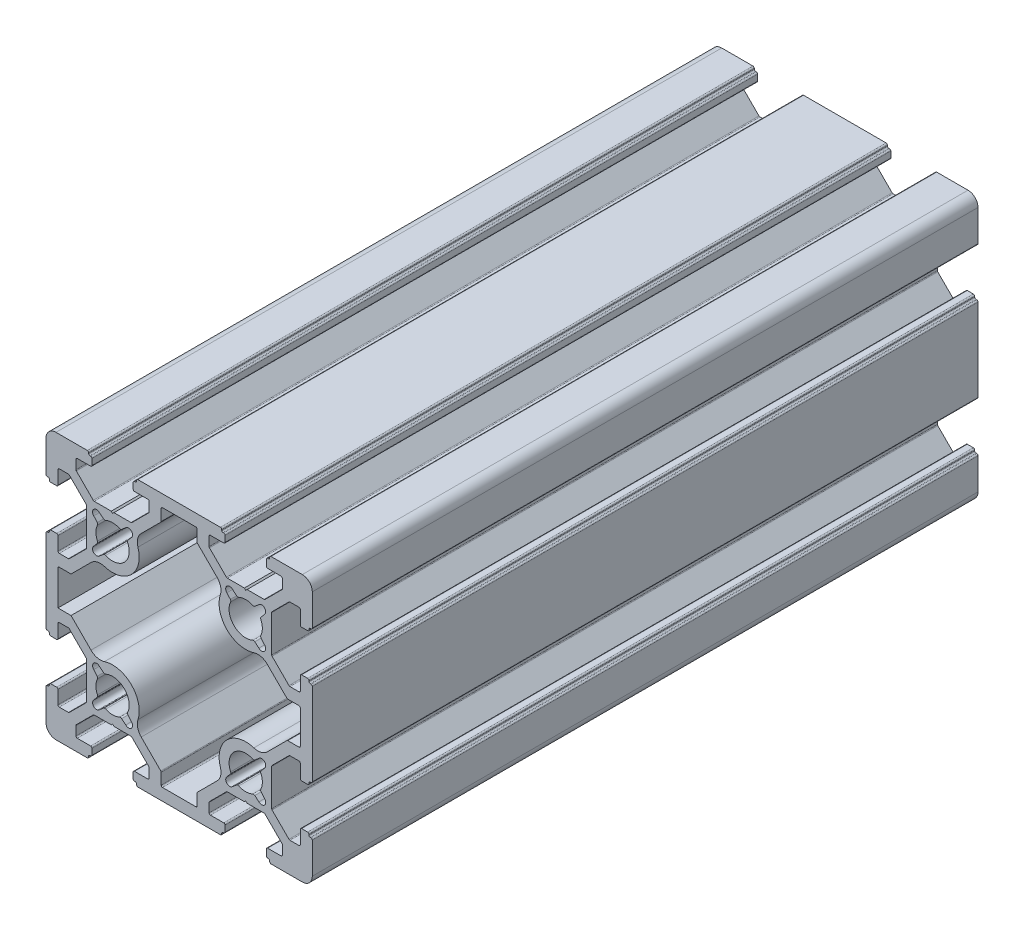
SolidWorks part; units mm, degrees
ref_plane "前视基准面" through (0, 0, 0) normal (0, 0, 1) x (1, 0, 0)
ref_plane "上视基准面" through (0, 0, 0) normal (0, 1, 0) x (1, 0, 0)
ref_plane "右视基准面" through (0, 0, 0) normal (1, 0, 0) x (0, 0, -1)
sketch "草图1" plane through (0, 0, 0) normal (0, 0, 1) x (1, 0, 0)
  line B0 (42.4612, 11.6) -> (43.3612, 11.6)
  line B1 (43.5612, 11.8) -> (43.5612, 11.9)
  line B2 (43.7612, 12.1) -> (43.8612, 12.1)
  line B3 (44.0612, 12.3) -> (44.0612, 24.7)
  line B4 (43.8612, 24.9) -> (43.7612, 24.9)
  line B5 (43.5612, 25.1) -> (43.5612, 25.2)
  line B6 (43.3612, 25.4) -> (42.4612, 25.4)
  line B7 (42.2612, 25.2) -> (42.2612, 23.2)
  line B8 (42.0612, 23) -> (40.7047, 23)
  line B9 (40.5633, 23.0586) -> (38.0198, 25.6021)
  line B10 (37.9612, 25.7435) -> (37.9612, 31.2565)
  line B11 (38.0198, 31.3979) -> (40.5633, 33.9414)
  line B12 (40.7047, 34) -> (42.0612, 34)
  line B13 (42.2612, 33.8) -> (42.2612, 31.8)
  line B14 (42.4612, 31.6) -> (43.3612, 31.6)
  line B15 (43.5612, 31.8) -> (43.5612, 31.9)
  line B16 (43.7612, 32.1) -> (43.8612, 32.1)
  line B17 (44.0612, 32.3) -> (44.0612, 37)
  line B18 (42.5612, 38.5) -> (37.8612, 38.5)
  line B19 (37.6612, 38.3) -> (37.6612, 38.2)
  line B20 (37.4612, 38) -> (37.3612, 38)
  line B21 (37.1612, 37.8) -> (37.1612, 36.9)
  line B22 (37.3612, 36.7) -> (39.3612, 36.7)
  line B23 (39.5612, 36.5) -> (39.5612, 35.1435)
  line B24 (39.5026, 35.0021) -> (36.9591, 32.4586)
  line B25 (36.8177, 32.4) -> (34.2612, 32.4)
  line B26 (34.2612, 32.4) -> (34.0612, 32.2)
  line B27 (34.0612, 32.2) -> (33.8612, 32.4)
  line B28 (33.8612, 32.4) -> (31.3047, 32.4)
  line B29 (31.1633, 32.4586) -> (28.6198, 35.0021)
  line B30 (28.5612, 35.1435) -> (28.5612, 36.5)
  line B31 (28.7612, 36.7) -> (30.7612, 36.7)
  line B32 (30.9612, 36.9) -> (30.9612, 37.8)
  line B33 (30.7612, 38) -> (30.6612, 38)
  line B34 (30.4612, 38.2) -> (30.4612, 38.3)
  line B35 (30.2612, 38.5) -> (17.8612, 38.5)
  line B36 (17.6612, 38.3) -> (17.6612, 38.2)
  line B37 (17.4612, 38) -> (17.3612, 38)
  line B38 (17.1612, 37.8) -> (17.1612, 36.9)
  line B39 (17.3612, 36.7) -> (19.3612, 36.7)
  line B40 (19.5612, 36.5) -> (19.5612, 35.1435)
  line B41 (19.5026, 35.0021) -> (16.9591, 32.4586)
  line B42 (16.8177, 32.4) -> (14.2612, 32.4)
  line B43 (14.2612, 32.4) -> (14.0612, 32.2)
  line B44 (14.0612, 32.2) -> (13.8612, 32.4)
  line B45 (13.8612, 32.4) -> (11.3047, 32.4)
  line B46 (11.1633, 32.4586) -> (8.6198, 35.0021)
  line B47 (8.5612, 35.1435) -> (8.5612, 36.5)
  line B48 (8.7612, 36.7) -> (10.7612, 36.7)
  line B49 (10.9612, 36.9) -> (10.9612, 37.8)
  line B50 (10.7612, 38) -> (10.6612, 38)
  line B51 (10.4612, 38.2) -> (10.4612, 38.3)
  line B52 (10.2612, 38.5) -> (5.5612, 38.5)
  line B53 (4.0612, 37) -> (4.0612, 32.3)
  line B54 (4.2612, 32.1) -> (4.3612, 32.1)
  line B55 (4.5612, 31.9) -> (4.5612, 31.8)
  line B56 (4.7612, 31.6) -> (5.6612, 31.6)
  line B57 (5.8612, 31.8) -> (5.8612, 33.8)
  line B58 (6.0612, 34) -> (7.4177, 34)
  line B59 (7.5591, 33.9414) -> (10.1026, 31.3979)
  line B60 (10.1612, 31.2565) -> (10.1612, 25.7435)
  line B61 (10.1026, 25.6021) -> (7.5591, 23.0586)
  line B62 (7.4177, 23) -> (6.0612, 23)
  line B63 (5.8612, 23.2) -> (5.8612, 25.2)
  line B64 (5.6612, 25.4) -> (4.7612, 25.4)
  line B65 (4.5612, 25.2) -> (4.5612, 25.1)
  line B66 (4.3612, 24.9) -> (4.2612, 24.9)
  line B67 (4.0612, 24.7) -> (4.0612, 12.3)
  line B68 (4.2612, 12.1) -> (4.3612, 12.1)
  line B69 (4.5612, 11.9) -> (4.5612, 11.8)
  line B70 (4.7612, 11.6) -> (5.6612, 11.6)
  line B71 (5.8612, 11.8) -> (5.8612, 13.8)
  line B72 (6.0612, 14) -> (7.4177, 14)
  line B73 (7.5591, 13.9414) -> (10.1026, 11.3979)
  line B74 (10.1612, 11.2565) -> (10.1612, 5.7435)
  line B75 (10.1026, 5.6021) -> (7.5591, 3.0586)
  line B76 (7.4177, 3) -> (6.0612, 3)
  line B77 (5.8612, 3.2) -> (5.8612, 5.2)
  line B78 (5.6612, 5.4) -> (4.7612, 5.4)
  line B79 (4.5612, 5.2) -> (4.5612, 5.1)
  line B80 (4.3612, 4.9) -> (4.2612, 4.9)
  line B81 (4.0612, 4.7) -> (4.0612, 0)
  line B82 (5.5612, -1.5) -> (10.2612, -1.5)
  line B83 (10.4612, -1.3) -> (10.4612, -1.2)
  line B84 (10.6612, -1) -> (10.7612, -1)
  line B85 (10.9612, -0.8) -> (10.9612, 0.1)
  line B86 (10.7612, 0.3) -> (8.7612, 0.3)
  line B87 (8.5612, 0.5) -> (8.5612, 1.8565)
  line B88 (8.6198, 1.9979) -> (11.1633, 4.5414)
  line B89 (11.3047, 4.6) -> (13.8612, 4.6)
  line B90 (13.8612, 4.6) -> (14.0612, 4.8)
  line B91 (14.0612, 4.8) -> (14.2612, 4.6)
  line B92 (14.2612, 4.6) -> (16.8177, 4.6)
  line B93 (16.9591, 4.5414) -> (19.5026, 1.9979)
  line B94 (19.5612, 1.8565) -> (19.5612, 0.5)
  line B95 (19.3612, 0.3) -> (17.3612, 0.3)
  line B96 (17.1612, 0.1) -> (17.1612, -0.8)
  line B97 (17.3612, -1) -> (17.4612, -1)
  line B98 (17.6612, -1.2) -> (17.6612, -1.3)
  line B99 (17.8612, -1.5) -> (30.2612, -1.5)
  line B100 (30.4612, -1.3) -> (30.4612, -1.2)
  line B101 (30.6612, -1) -> (30.7612, -1)
  line B102 (30.9612, -0.8) -> (30.9612, 0.1)
  line B103 (30.7612, 0.3) -> (28.7612, 0.3)
  line B104 (28.5612, 0.5) -> (28.5612, 1.8565)
  line B105 (28.6198, 1.9979) -> (31.1633, 4.5414)
  line B106 (31.3047, 4.6) -> (33.8612, 4.6)
  line B107 (33.8612, 4.6) -> (34.0612, 4.8)
  line B108 (34.0612, 4.8) -> (34.2612, 4.6)
  line B109 (34.2612, 4.6) -> (36.8177, 4.6)
  line B110 (36.9591, 4.5414) -> (39.5026, 1.9979)
  line B111 (39.5612, 1.8565) -> (39.5612, 0.5)
  line B112 (39.3612, 0.3) -> (37.3612, 0.3)
  line B113 (37.1612, 0.1) -> (37.1612, -0.8)
  line B114 (37.3612, -1) -> (37.4612, -1)
  line B115 (37.6612, -1.2) -> (37.6612, -1.3)
  line B116 (37.8612, -1.5) -> (42.5612, -1.5)
  line B117 (44.0612, 0) -> (44.0612, 4.7)
  line B118 (43.8612, 4.9) -> (43.7612, 4.9)
  line B119 (43.5612, 5.1) -> (43.5612, 5.2)
  line B120 (43.3612, 5.4) -> (42.4612, 5.4)
  line B121 (42.2612, 5.2) -> (42.2612, 3.2)
  line B122 (42.0612, 3) -> (40.7047, 3)
  line B123 (40.5633, 3.0586) -> (38.0198, 5.6021)
  line B124 (37.9612, 5.7435) -> (37.9612, 11.2565)
  line B125 (38.0198, 11.3979) -> (40.5633, 13.9414)
  line B126 (40.7047, 14) -> (42.0612, 14)
  line B127 (42.2612, 13.8) -> (42.2612, 11.8)
  line B128 (31.7484, 7.1346) -> (31.2328, 6.5201)
  line B129 (32.0813, 5.6716) -> (32.6958, 6.1872)
  line B130 (35.4266, 6.1872) -> (36.0411, 5.6716)
  line B131 (36.8896, 6.5201) -> (36.374, 7.1346)
  line B132 (36.374, 9.8654) -> (36.8896, 10.4799)
  line B133 (36.0411, 11.3284) -> (35.4266, 10.8128)
  line B134 (35.4266, 26.1872) -> (36.0411, 25.6716)
  line B135 (36.8896, 26.5201) -> (36.374, 27.1346)
  line B136 (36.374, 29.8654) -> (36.8896, 30.4799)
  line B137 (36.0411, 31.3284) -> (35.4266, 30.8128)
  line B138 (32.6958, 30.8128) -> (32.0813, 31.3284)
  line B139 (31.2328, 30.4799) -> (31.7484, 29.8654)
  line B140 (42.2612, 16) -> (42.2612, 21)
  line B141 (42.0612, 21.2) -> (40.3834, 21.2)
  line B142 (40.242, 21.2586) -> (37.3016, 24.1989)
  line B143 (29.7601, 31.7404) -> (26.8198, 34.6808)
  line B144 (26.7612, 34.8222) -> (26.7612, 36.5)
  line B145 (26.5612, 36.7) -> (21.5612, 36.7)
  line B146 (21.3612, 36.5) -> (21.3612, 34.8222)
  line B147 (21.3026, 34.6808) -> (18.3623, 31.7404)
  line B148 (10.8207, 24.1989) -> (7.8804, 21.2586)
  line B149 (7.739, 21.2) -> (6.0612, 21.2)
  line B150 (5.8612, 21) -> (5.8612, 15.8)
  line B151 (5.8612, 15.8) -> (7.8219, 15.8)
  line B152 (7.8219, 15.8) -> (10.8207, 12.8011)
  line B153 (18.3623, 5.2596) -> (21.3026, 2.3192)
  line B154 (21.3612, 2.1778) -> (21.3612, 0.5)
  line B155 (21.5612, 0.3) -> (26.5612, 0.3)
  line B156 (26.7612, 0.5) -> (26.7612, 2.1778)
  line B157 (26.8198, 2.3192) -> (29.7601, 5.2596)
  line B158 (37.3016, 12.8011) -> (40.242, 15.7414)
  line B159 (40.3834, 15.8) -> (42.0612, 15.8)
  line B160 (12.6958, 10.8128) -> (12.0813, 11.3284)
  line B161 (11.2328, 10.4799) -> (11.7484, 9.8654)
  line B162 (11.7484, 7.1346) -> (11.2328, 6.5201)
  line B163 (12.0813, 5.6716) -> (12.6958, 6.1872)
  line B164 (15.4266, 6.1872) -> (16.0411, 5.6716)
  line B165 (16.8896, 6.5201) -> (16.374, 7.1346)
  line B166 (16.374, 29.8654) -> (16.8896, 30.4799)
  line B167 (16.0411, 31.3284) -> (15.4266, 30.8128)
  line B168 (12.6958, 30.8128) -> (12.0813, 31.3284)
  line B169 (11.2328, 30.4799) -> (11.7484, 29.8654)
  line B170 (11.7484, 27.1346) -> (11.2328, 26.5201)
  line B171 (12.0813, 25.6716) -> (12.6958, 26.1872)
  arc B172 (42.2612, 11.8) -> (42.4612, 11.6) centre (42.4612, 11.8) ccw
  arc B173 (43.3612, 11.6) -> (43.5612, 11.8) centre (43.3612, 11.8) ccw
  arc B174 (43.7612, 12.1) -> (43.5612, 11.9) centre (43.7612, 11.9) ccw
  arc B175 (43.8612, 12.1) -> (44.0612, 12.3) centre (43.8612, 12.3) ccw
  arc B176 (44.0612, 24.7) -> (43.8612, 24.9) centre (43.8612, 24.7) ccw
  arc B177 (43.5612, 25.1) -> (43.7612, 24.9) centre (43.7612, 25.1) ccw
  arc B178 (43.5612, 25.2) -> (43.3612, 25.4) centre (43.3612, 25.2) ccw
  arc B179 (42.4612, 25.4) -> (42.2612, 25.2) centre (42.4612, 25.2) ccw
  arc B180 (42.0612, 23) -> (42.2612, 23.2) centre (42.0612, 23.2) ccw
  arc B181 (40.5633, 23.0586) -> (40.7047, 23) centre (40.7047, 23.2) ccw
  arc B182 (37.9612, 25.7435) -> (38.0198, 25.6021) centre (38.1612, 25.7435) ccw
  arc B183 (38.0198, 31.3979) -> (37.9612, 31.2565) centre (38.1612, 31.2565) ccw
  arc B184 (40.7047, 34) -> (40.5633, 33.9414) centre (40.7047, 33.8) ccw
  arc B185 (42.2612, 33.8) -> (42.0612, 34) centre (42.0612, 33.8) ccw
  arc B186 (42.2612, 31.8) -> (42.4612, 31.6) centre (42.4612, 31.8) ccw
  arc B187 (43.3612, 31.6) -> (43.5612, 31.8) centre (43.3612, 31.8) ccw
  arc B188 (43.7612, 32.1) -> (43.5612, 31.9) centre (43.7612, 31.9) ccw
  arc B189 (43.8612, 32.1) -> (44.0612, 32.3) centre (43.8612, 32.3) ccw
  arc B190 (44.0612, 37) -> (42.5612, 38.5) centre (42.5612, 37) ccw
  arc B191 (37.8612, 38.5) -> (37.6612, 38.3) centre (37.8612, 38.3) ccw
  arc B192 (37.4612, 38) -> (37.6612, 38.2) centre (37.4612, 38.2) ccw
  arc B193 (37.3612, 38) -> (37.1612, 37.8) centre (37.3612, 37.8) ccw
  arc B194 (37.1612, 36.9) -> (37.3612, 36.7) centre (37.3612, 36.9) ccw
  arc B195 (39.5612, 36.5) -> (39.3612, 36.7) centre (39.3612, 36.5) ccw
  arc B196 (39.5026, 35.0021) -> (39.5612, 35.1435) centre (39.3612, 35.1435) ccw
  arc B197 (36.8177, 32.4) -> (36.9591, 32.4586) centre (36.8177, 32.6) ccw
  arc B198 (31.1633, 32.4586) -> (31.3047, 32.4) centre (31.3047, 32.6) ccw
  arc B199 (28.5612, 35.1435) -> (28.6198, 35.0021) centre (28.7612, 35.1435) ccw
  arc B200 (28.7612, 36.7) -> (28.5612, 36.5) centre (28.7612, 36.5) ccw
  arc B201 (30.7612, 36.7) -> (30.9612, 36.9) centre (30.7612, 36.9) ccw
  arc B202 (30.9612, 37.8) -> (30.7612, 38) centre (30.7612, 37.8) ccw
  arc B203 (30.4612, 38.2) -> (30.6612, 38) centre (30.6612, 38.2) ccw
  arc B204 (30.4612, 38.3) -> (30.2612, 38.5) centre (30.2612, 38.3) ccw
  arc B205 (17.8612, 38.5) -> (17.6612, 38.3) centre (17.8612, 38.3) ccw
  arc B206 (17.4612, 38) -> (17.6612, 38.2) centre (17.4612, 38.2) ccw
  arc B207 (17.3612, 38) -> (17.1612, 37.8) centre (17.3612, 37.8) ccw
  arc B208 (17.1612, 36.9) -> (17.3612, 36.7) centre (17.3612, 36.9) ccw
  arc B209 (19.5612, 36.5) -> (19.3612, 36.7) centre (19.3612, 36.5) ccw
  arc B210 (19.5026, 35.0021) -> (19.5612, 35.1435) centre (19.3612, 35.1435) ccw
  arc B211 (16.8177, 32.4) -> (16.9591, 32.4586) centre (16.8177, 32.6) ccw
  arc B212 (11.1633, 32.4586) -> (11.3047, 32.4) centre (11.3047, 32.6) ccw
  arc B213 (8.5612, 35.1435) -> (8.6198, 35.0021) centre (8.7612, 35.1435) ccw
  arc B214 (8.7612, 36.7) -> (8.5612, 36.5) centre (8.7612, 36.5) ccw
  arc B215 (10.7612, 36.7) -> (10.9612, 36.9) centre (10.7612, 36.9) ccw
  arc B216 (10.9612, 37.8) -> (10.7612, 38) centre (10.7612, 37.8) ccw
  arc B217 (10.4612, 38.2) -> (10.6612, 38) centre (10.6612, 38.2) ccw
  arc B218 (10.4612, 38.3) -> (10.2612, 38.5) centre (10.2612, 38.3) ccw
  arc B219 (5.5612, 38.5) -> (4.0612, 37) centre (5.5612, 37) ccw
  arc B220 (4.0612, 32.3) -> (4.2612, 32.1) centre (4.2612, 32.3) ccw
  arc B221 (4.5612, 31.9) -> (4.3612, 32.1) centre (4.3612, 31.9) ccw
  arc B222 (4.5612, 31.8) -> (4.7612, 31.6) centre (4.7612, 31.8) ccw
  arc B223 (5.6612, 31.6) -> (5.8612, 31.8) centre (5.6612, 31.8) ccw
  arc B224 (6.0612, 34) -> (5.8612, 33.8) centre (6.0612, 33.8) ccw
  arc B225 (7.5591, 33.9414) -> (7.4177, 34) centre (7.4177, 33.8) ccw
  arc B226 (10.1612, 31.2565) -> (10.1026, 31.3979) centre (9.9612, 31.2565) ccw
  arc B227 (10.1026, 25.6021) -> (10.1612, 25.7435) centre (9.9612, 25.7435) ccw
  arc B228 (7.4177, 23) -> (7.5591, 23.0586) centre (7.4177, 23.2) ccw
  arc B229 (5.8612, 23.2) -> (6.0612, 23) centre (6.0612, 23.2) ccw
  arc B230 (5.8612, 25.2) -> (5.6612, 25.4) centre (5.6612, 25.2) ccw
  arc B231 (4.7612, 25.4) -> (4.5612, 25.2) centre (4.7612, 25.2) ccw
  arc B232 (4.3612, 24.9) -> (4.5612, 25.1) centre (4.3612, 25.1) ccw
  arc B233 (4.2612, 24.9) -> (4.0612, 24.7) centre (4.2612, 24.7) ccw
  arc B234 (4.0612, 12.3) -> (4.2612, 12.1) centre (4.2612, 12.3) ccw
  arc B235 (4.5612, 11.9) -> (4.3612, 12.1) centre (4.3612, 11.9) ccw
  arc B236 (4.5612, 11.8) -> (4.7612, 11.6) centre (4.7612, 11.8) ccw
  arc B237 (5.6612, 11.6) -> (5.8612, 11.8) centre (5.6612, 11.8) ccw
  arc B238 (6.0612, 14) -> (5.8612, 13.8) centre (6.0612, 13.8) ccw
  arc B239 (7.5591, 13.9414) -> (7.4177, 14) centre (7.4177, 13.8) ccw
  arc B240 (10.1612, 11.2565) -> (10.1026, 11.3979) centre (9.9612, 11.2565) ccw
  arc B241 (10.1026, 5.6021) -> (10.1612, 5.7435) centre (9.9612, 5.7435) ccw
  arc B242 (7.4177, 3) -> (7.5591, 3.0586) centre (7.4177, 3.2) ccw
  arc B243 (5.8612, 3.2) -> (6.0612, 3) centre (6.0612, 3.2) ccw
  arc B244 (5.8612, 5.2) -> (5.6612, 5.4) centre (5.6612, 5.2) ccw
  arc B245 (4.7612, 5.4) -> (4.5612, 5.2) centre (4.7612, 5.2) ccw
  arc B246 (4.3612, 4.9) -> (4.5612, 5.1) centre (4.3612, 5.1) ccw
  arc B247 (4.2612, 4.9) -> (4.0612, 4.7) centre (4.2612, 4.7) ccw
  arc B248 (4.0612, 0) -> (5.5612, -1.5) centre (5.5612, 0) ccw
  arc B249 (10.2612, -1.5) -> (10.4612, -1.3) centre (10.2612, -1.3) ccw
  arc B250 (10.6612, -1) -> (10.4612, -1.2) centre (10.6612, -1.2) ccw
  arc B251 (10.7612, -1) -> (10.9612, -0.8) centre (10.7612, -0.8) ccw
  arc B252 (10.9612, 0.1) -> (10.7612, 0.3) centre (10.7612, 0.1) ccw
  arc B253 (8.5612, 0.5) -> (8.7612, 0.3) centre (8.7612, 0.5) ccw
  arc B254 (8.6198, 1.9979) -> (8.5612, 1.8565) centre (8.7612, 1.8565) ccw
  arc B255 (11.3047, 4.6) -> (11.1633, 4.5414) centre (11.3047, 4.4) ccw
  arc B256 (16.9591, 4.5414) -> (16.8177, 4.6) centre (16.8177, 4.4) ccw
  arc B257 (19.5612, 1.8565) -> (19.5026, 1.9979) centre (19.3612, 1.8565) ccw
  arc B258 (19.3612, 0.3) -> (19.5612, 0.5) centre (19.3612, 0.5) ccw
  arc B259 (17.3612, 0.3) -> (17.1612, 0.1) centre (17.3612, 0.1) ccw
  arc B260 (17.1612, -0.8) -> (17.3612, -1) centre (17.3612, -0.8) ccw
  arc B261 (17.6612, -1.2) -> (17.4612, -1) centre (17.4612, -1.2) ccw
  arc B262 (17.6612, -1.3) -> (17.8612, -1.5) centre (17.8612, -1.3) ccw
  arc B263 (30.2612, -1.5) -> (30.4612, -1.3) centre (30.2612, -1.3) ccw
  arc B264 (30.6612, -1) -> (30.4612, -1.2) centre (30.6612, -1.2) ccw
  arc B265 (30.7612, -1) -> (30.9612, -0.8) centre (30.7612, -0.8) ccw
  arc B266 (30.9612, 0.1) -> (30.7612, 0.3) centre (30.7612, 0.1) ccw
  arc B267 (28.5612, 0.5) -> (28.7612, 0.3) centre (28.7612, 0.5) ccw
  arc B268 (28.6198, 1.9979) -> (28.5612, 1.8565) centre (28.7612, 1.8565) ccw
  arc B269 (31.3047, 4.6) -> (31.1633, 4.5414) centre (31.3047, 4.4) ccw
  arc B270 (36.9591, 4.5414) -> (36.8177, 4.6) centre (36.8177, 4.4) ccw
  arc B271 (39.5612, 1.8565) -> (39.5026, 1.9979) centre (39.3612, 1.8565) ccw
  arc B272 (39.3612, 0.3) -> (39.5612, 0.5) centre (39.3612, 0.5) ccw
  arc B273 (37.3612, 0.3) -> (37.1612, 0.1) centre (37.3612, 0.1) ccw
  arc B274 (37.1612, -0.8) -> (37.3612, -1) centre (37.3612, -0.8) ccw
  arc B275 (37.6612, -1.2) -> (37.4612, -1) centre (37.4612, -1.2) ccw
  arc B276 (37.6612, -1.3) -> (37.8612, -1.5) centre (37.8612, -1.3) ccw
  arc B277 (42.5612, -1.5) -> (44.0612, 0) centre (42.5612, 0) ccw
  arc B278 (44.0612, 4.7) -> (43.8612, 4.9) centre (43.8612, 4.7) ccw
  arc B279 (43.5612, 5.1) -> (43.7612, 4.9) centre (43.7612, 5.1) ccw
  arc B280 (43.5612, 5.2) -> (43.3612, 5.4) centre (43.3612, 5.2) ccw
  arc B281 (42.4612, 5.4) -> (42.2612, 5.2) centre (42.4612, 5.2) ccw
  arc B282 (42.0612, 3) -> (42.2612, 3.2) centre (42.0612, 3.2) ccw
  arc B283 (40.5633, 3.0586) -> (40.7047, 3) centre (40.7047, 3.2) ccw
  arc B284 (37.9612, 5.7435) -> (38.0198, 5.6021) centre (38.1612, 5.7435) ccw
  arc B285 (38.0198, 11.3979) -> (37.9612, 11.2565) centre (38.1612, 11.2565) ccw
  arc B286 (40.7047, 14) -> (40.5633, 13.9414) centre (40.7047, 13.8) ccw
  arc B287 (42.2612, 13.8) -> (42.0612, 14) centre (42.0612, 13.8) ccw
  arc B288 (35.1082, 10.7702) -> (35.4266, 10.8128) centre (35.2338, 11.0426) ccw
  arc B289 (35.1082, 10.7702) -> (31.791, 7.453) centre (34.0612, 8.5) ccw
  arc B290 (31.7484, 7.1346) -> (31.791, 7.453) centre (31.5186, 7.3274) ccw
  arc B291 (31.2328, 6.5201) -> (32.0813, 5.6716) centre (31.657, 6.0958) ccw
  arc B292 (33.0142, 6.2298) -> (32.6958, 6.1872) centre (32.8886, 5.9574) ccw
  arc B293 (33.0142, 6.2298) -> (35.1082, 6.2298) centre (34.0612, 8.5) ccw
  arc B294 (35.4266, 6.1872) -> (35.1082, 6.2298) centre (35.2338, 5.9574) ccw
  arc B295 (36.0411, 5.6716) -> (36.8896, 6.5201) centre (36.4654, 6.0958) ccw
  arc B296 (36.3314, 7.453) -> (36.374, 7.1346) centre (36.6038, 7.3274) ccw
  arc B297 (36.3314, 7.453) -> (36.3314, 9.547) centre (34.0612, 8.5) ccw
  arc B298 (36.374, 9.8654) -> (36.3314, 9.547) centre (36.6038, 9.6726) ccw
  arc B299 (36.8896, 10.4799) -> (36.0411, 11.3284) centre (36.4654, 10.9042) ccw
  arc B300 (35.4266, 26.1872) -> (35.1082, 26.2298) centre (35.2338, 25.9574) ccw
  arc B301 (36.0411, 25.6716) -> (36.8896, 26.5201) centre (36.4654, 26.0958) ccw
  arc B302 (36.3314, 27.453) -> (36.374, 27.1346) centre (36.6038, 27.3274) ccw
  arc B303 (36.3314, 27.453) -> (36.3314, 29.547) centre (34.0612, 28.5) ccw
  arc B304 (36.374, 29.8654) -> (36.3314, 29.547) centre (36.6038, 29.6726) ccw
  arc B305 (36.8896, 30.4799) -> (36.0411, 31.3284) centre (36.4654, 30.9042) ccw
  arc B306 (35.1082, 30.7702) -> (35.4266, 30.8128) centre (35.2338, 31.0426) ccw
  arc B307 (35.1082, 30.7702) -> (33.0142, 30.7702) centre (34.0612, 28.5) ccw
  arc B308 (32.6958, 30.8128) -> (33.0142, 30.7702) centre (32.8886, 31.0426) ccw
  arc B309 (32.0813, 31.3284) -> (31.2328, 30.4799) centre (31.657, 30.9042) ccw
  arc B310 (31.791, 29.547) -> (31.7484, 29.8654) centre (31.5186, 29.6726) ccw
  arc B311 (31.791, 29.547) -> (35.1082, 26.2298) centre (34.0612, 28.5) ccw
  arc B312 (42.2612, 21) -> (42.0612, 21.2) centre (42.0612, 21) ccw
  arc B313 (40.242, 21.2586) -> (40.3834, 21.2) centre (40.3834, 21.4) ccw
  arc B314 (37.3016, 24.1989) -> (35.2787, 24.6898) centre (35.8874, 22.7847) ccw
  arc B315 (30.251, 29.7175) -> (35.2787, 24.6898) centre (34.0612, 28.5) ccw
  arc B316 (30.251, 29.7175) -> (29.7601, 31.7404) centre (28.3459, 30.3262) ccw
  arc B317 (26.7612, 34.8222) -> (26.8198, 34.6808) centre (26.9612, 34.8222) ccw
  arc B318 (26.7612, 36.5) -> (26.5612, 36.7) centre (26.5612, 36.5) ccw
  arc B319 (21.5612, 36.7) -> (21.3612, 36.5) centre (21.5612, 36.5) ccw
  arc B320 (21.3026, 34.6808) -> (21.3612, 34.8222) centre (21.1612, 34.8222) ccw
  arc B321 (18.3623, 31.7404) -> (17.8714, 29.7175) centre (19.7765, 30.3262) ccw
  arc B322 (12.8437, 24.6898) -> (17.8714, 29.7175) centre (14.0612, 28.5) ccw
  arc B323 (12.8437, 24.6898) -> (10.8207, 24.1989) centre (12.235, 22.7847) ccw
  arc B324 (7.739, 21.2) -> (7.8804, 21.2586) centre (7.739, 21.4) ccw
  arc B325 (6.0612, 21.2) -> (5.8612, 21) centre (6.0612, 21) ccw
  arc B326 (10.8207, 12.8011) -> (12.8437, 12.3102) centre (12.235, 14.2153) ccw
  arc B327 (17.8714, 7.2825) -> (12.8437, 12.3102) centre (14.0612, 8.5) ccw
  arc B328 (17.8714, 7.2825) -> (18.3623, 5.2596) centre (19.7765, 6.6738) ccw
  arc B329 (21.3612, 2.1778) -> (21.3026, 2.3192) centre (21.1612, 2.1778) ccw
  arc B330 (21.3612, 0.5) -> (21.5612, 0.3) centre (21.5612, 0.5) ccw
  arc B331 (26.5612, 0.3) -> (26.7612, 0.5) centre (26.5612, 0.5) ccw
  arc B332 (26.8198, 2.3192) -> (26.7612, 2.1778) centre (26.9612, 2.1778) ccw
  arc B333 (29.7601, 5.2596) -> (30.251, 7.2825) centre (28.3459, 6.6738) ccw
  arc B334 (35.2787, 12.3102) -> (30.251, 7.2825) centre (34.0612, 8.5) ccw
  arc B335 (35.2787, 12.3102) -> (37.3016, 12.8011) centre (35.8874, 14.2153) ccw
  arc B336 (40.3834, 15.8) -> (40.242, 15.7414) centre (40.3834, 15.6) ccw
  arc B337 (42.0612, 15.8) -> (42.2612, 16) centre (42.0612, 16) ccw
  arc B338 (12.6958, 10.8128) -> (13.0142, 10.7702) centre (12.8886, 11.0426) ccw
  arc B339 (12.0813, 11.3284) -> (11.2328, 10.4799) centre (11.657, 10.9042) ccw
  arc B340 (11.791, 9.547) -> (11.7484, 9.8654) centre (11.5186, 9.6726) ccw
  arc B341 (11.791, 9.547) -> (11.791, 7.453) centre (14.0612, 8.5) ccw
  arc B342 (11.7484, 7.1346) -> (11.791, 7.453) centre (11.5186, 7.3274) ccw
  arc B343 (11.2328, 6.5201) -> (12.0813, 5.6716) centre (11.657, 6.0958) ccw
  arc B344 (13.0142, 6.2298) -> (12.6958, 6.1872) centre (12.8886, 5.9574) ccw
  arc B345 (13.0142, 6.2298) -> (15.1082, 6.2298) centre (14.0612, 8.5) ccw
  arc B346 (15.4266, 6.1872) -> (15.1082, 6.2298) centre (15.2338, 5.9574) ccw
  arc B347 (16.0411, 5.6716) -> (16.8896, 6.5201) centre (16.4654, 6.0958) ccw
  arc B348 (16.3314, 7.453) -> (16.374, 7.1346) centre (16.6038, 7.3274) ccw
  arc B349 (16.3314, 7.453) -> (13.0142, 10.7702) centre (14.0612, 8.5) ccw
  arc B350 (13.0142, 26.2298) -> (12.6958, 26.1872) centre (12.8886, 25.9574) ccw
  arc B351 (13.0142, 26.2298) -> (16.3314, 29.547) centre (14.0612, 28.5) ccw
  arc B352 (16.374, 29.8654) -> (16.3314, 29.547) centre (16.6038, 29.6726) ccw
  arc B353 (16.8896, 30.4799) -> (16.0411, 31.3284) centre (16.4654, 30.9042) ccw
  arc B354 (15.1082, 30.7702) -> (15.4266, 30.8128) centre (15.2338, 31.0426) ccw
  arc B355 (15.1082, 30.7702) -> (13.0142, 30.7702) centre (14.0612, 28.5) ccw
  arc B356 (12.6958, 30.8128) -> (13.0142, 30.7702) centre (12.8886, 31.0426) ccw
  arc B357 (12.0813, 31.3284) -> (11.2328, 30.4799) centre (11.657, 30.9042) ccw
  arc B358 (11.791, 29.547) -> (11.7484, 29.8654) centre (11.5186, 29.6726) ccw
  arc B359 (11.791, 29.547) -> (11.791, 27.453) centre (14.0612, 28.5) ccw
  arc B360 (11.7484, 27.1346) -> (11.791, 27.453) centre (11.5186, 27.3274) ccw
  arc B361 (11.2328, 26.5201) -> (12.0813, 25.6716) centre (11.657, 26.0958) ccw
sketch_block_instance "A$C3032580A-1"
sketch_block "A$C3032580A"
extrude "凸台-拉伸1" add sketch "草图1" along normal blind 100
